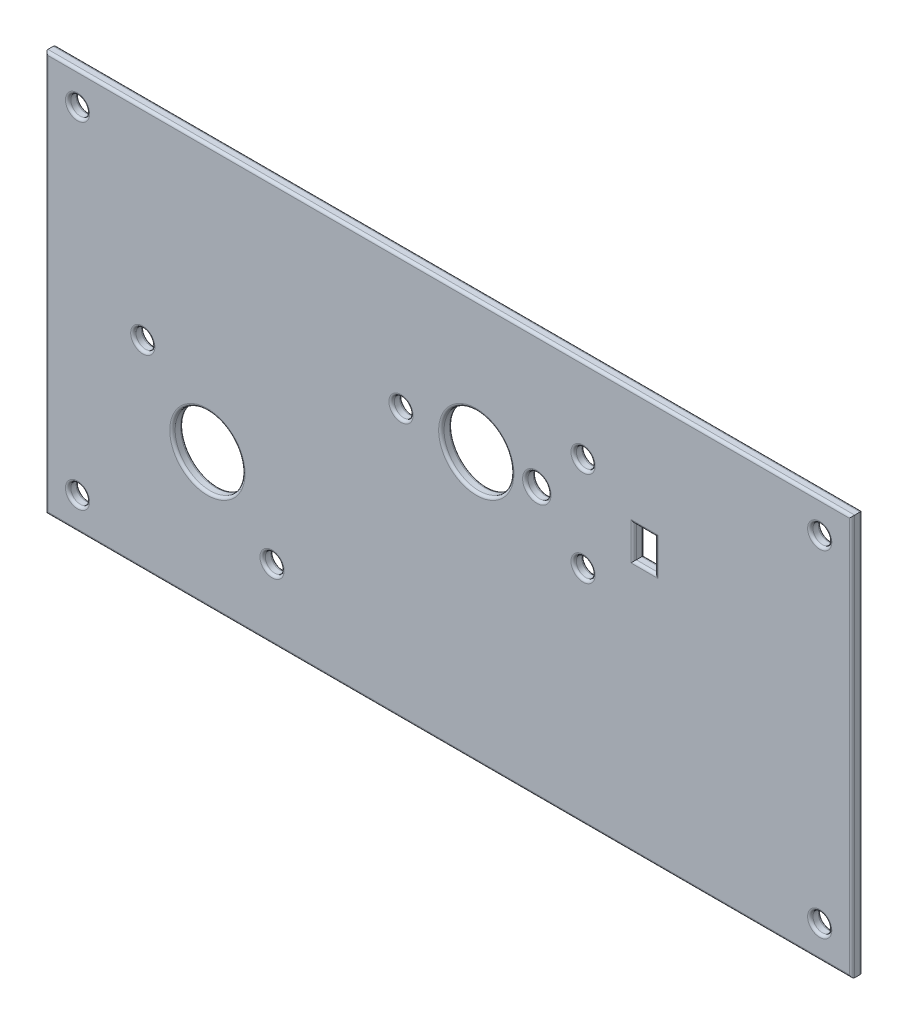
SolidWorks part; units mm, degrees
ref_plane "Front Plane" through (0, 0, 0) normal (0, 0, 1) x (1, 0, 0)
ref_plane "Top Plane" through (0, 0, 0) normal (0, 1, 0) x (1, 0, 0)
ref_plane "Right Plane" through (0, 0, 0) normal (1, 0, 0) x (0, 0, -1)
sketch "Sketch1" plane through (0, 0, 0) normal (0, 0, 1) x (1, 0, 0)
  line L0 (80.15, 50) -> (66.15, 50)
  line L1 (0, 0) -> (150, 0)
  line L2 (0, 0) -> (0, 74.5)
  line L3 (0, 74.5) -> (150, 74.5)
  line L4 (150, 0) -> (150, 74.5)
  line L5 (80.15, 50) -> (91.4, 50)
  line L6 (100, 50) -> (91.4, 50)
  line L7 (100, 58.8) -> (100, 41.2)
  line L8 (100, 50) -> (150, 50) construction
  line L9 (80.15, 50) -> (30.15, 50)
  line L10 (30.15, 50) -> (30.15, 25) construction
  line L11 (30.15, 25) -> (30.15, 0) construction
  line L12 (0, 6) -> (6, 6) construction
  line L13 (6, 6) -> (6, 0) construction
  line L14 (6, 68.5) -> (6, 74.5) construction
  line L15 (6, 68.5) -> (0, 68.5) construction
  line L16 (144, 0) -> (144, 6) construction
  line L17 (144, 6) -> (150, 6) construction
  line L18 (150, 68.5) -> (144, 68.5) construction
  line L19 (91.4, 50) -> (109.4, 50)
  line L20 (30.15, 25) -> (18.1292, 37.0208)
  line L21 (30.15, 25) -> (42.1708, 12.9792)
  line L22 (109.4, 50) -> (109.4, 47)
  line L23 (109.4, 47) -> (113.4, 47)
  line L24 (113.4, 47) -> (113.4, 53)
  line L25 (113.4, 53) -> (109.4, 53)
  line L26 (109.4, 53) -> (109.4, 50)
  line L27 (144, 68.5) -> (144, 74.5) construction
  circle A0 centre (80.15, 50) radius 6.5
  circle A1 centre (66.15, 50) radius 1.75
  circle A2 centre (91.4, 50) radius 2.15
  circle A3 centre (100, 58.8) radius 1.75
  circle A4 centre (100, 41.2) radius 1.75
  circle A5 centre (30.15, 25) radius 11 construction
  circle A8 centre (6, 68.5) radius 1.75
  circle A9 centre (6, 6) radius 1.75
  circle A10 centre (18.1292, 37.0208) radius 1.75
  circle A11 centre (42.1708, 12.9792) radius 1.75
  circle A12 centre (30.15, 25) radius 6.5
  circle A15 centre (144, 68.5) radius 1.75
  circle A16 centre (144, 6) radius 1.75
  dimension "D3" = 13
  dimension "D5" = 3.5
  dimension "D6" = 4.3
  dimension "D14" = 22
  dimension "D15" = 3.5
  dimension "D19" = 3.5
  dimension "D20" = 13
  dimension "D1" = 74.5
  dimension "D2" = 150
  dimension "D4" = 14
  dimension "D7" = 11.25
  dimension "D8" = 8.6
  dimension "D9" = 17.6
  dimension "D10" = 50
  dimension "D11" = 50
  dimension "D12" = 50
  dimension "D13" = 25
  dimension "D16" = 6
  dimension "D17" = 45
  dimension "D18" = 17
  dimension "D24" = 18
  dimension "D25" = 3
  dimension "D26" = 4
extrude "Boss-Extrude1" add sketch "Sketch1" along normal blind 2
fillet "Fillet1" radius 0.5 40 edges at (150, 37.25, 0) (75, 74.5, 0) (0, 37.25, 0) (75, 0, 0) (101.75, 58.8, 0) (7.75, 68.5, 0) (7.75, 6, 0) (36.65, 25, 0) (109.4, 50, 0) (111.4, 53, 0) (113.4, 50, 0) (111.4, 47, 0) (86.65, 50, 0) (67.9, 50, 0) (93.55, 50, 0) (101.75, 41.2, 0) (43.9208, 12.9792, 0) (19.8792, 37.0208, 0) (0, 37.25, 2) (75, 74.5, 2) (150, 37.25, 2) (75, 0, 2) (101.75, 58.8, 2) (7.75, 68.5, 2) (7.75, 6, 2) (36.65, 25, 2) (113.4, 50, 2) (111.4, 53, 2) (109.4, 50, 2) (111.4, 47, 2) (86.65, 50, 2) (67.9, 50, 2) (93.55, 50, 2) (101.75, 41.2, 2) (43.9208, 12.9792, 2) (19.8792, 37.0208, 2) (145.75, 68.5, 0) (145.75, 6, 0) (145.75, 68.5, 2) (145.75, 6, 2)
